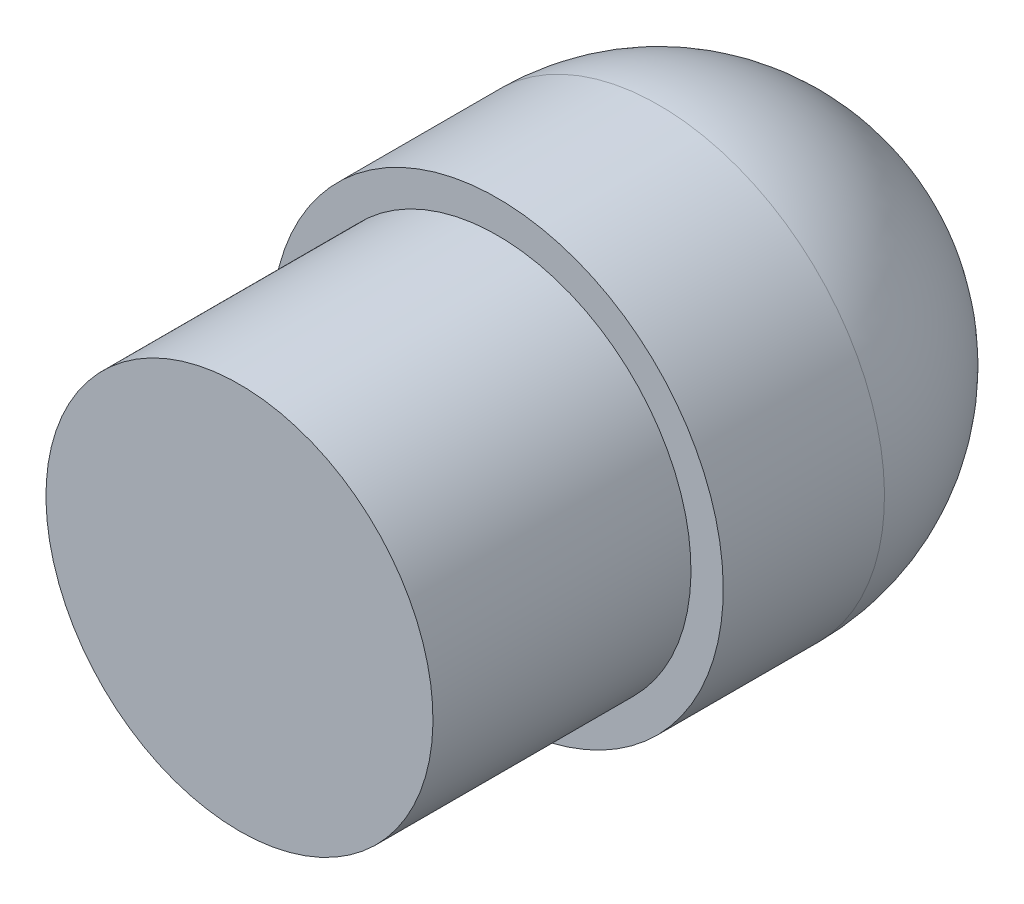
SolidWorks part; units mm, degrees
ref_plane "Alzado" through (0, 0, 0) normal (0, 0, 1) x (1, 0, 0)
ref_plane "Planta" through (0, 0, 0) normal (0, 1, 0) x (1, 0, 0)
ref_plane "Vista lateral" through (0, 0, 0) normal (1, 0, 0) x (0, 0, -1)
sketch "Croquis1" plane through (0, 0, 0) normal (1, 0, 0) x (0, 0, -1)
  line L0 (0, 0) -> (0, 15)
  line L1 (0, 15) -> (20, 15)
  line L2 (20, 15) -> (20, 17.5)
  line L3 (20, 17.5) -> (32.5, 17.5)
  line L4 (32.5, 17.5) -> (32.5, 0)
  line L6 (20, 15) -> (20, 0)
  line L7 (0, 0) -> (50, 0) construction
  arc A0 (50, 0) -> (32.5, 17.5) centre (32.5, 0) ccw
  dimension "D1" = 15
  dimension "D2" = 17.5
  dimension "D3" = 20
  dimension "D4" = 50
revolve "Revolución1" add sketch "Croquis1" angle 360 about L7
